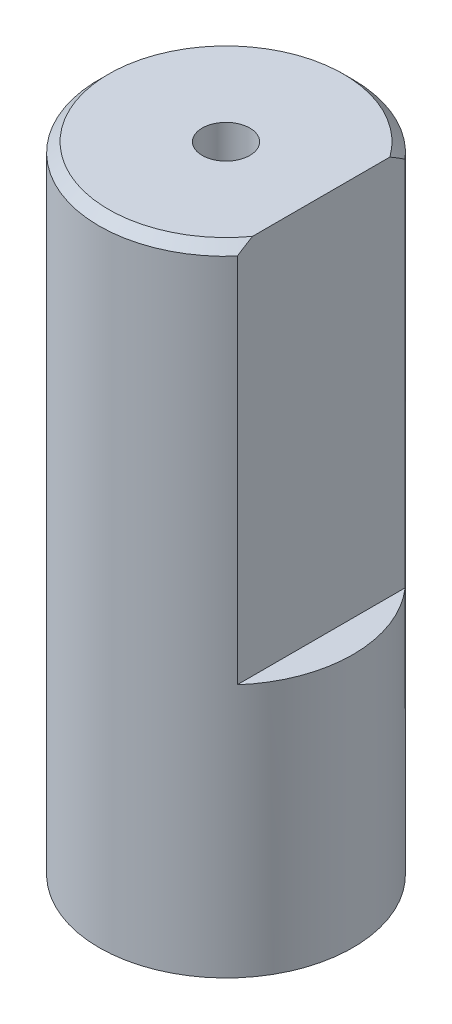
SolidWorks part; units mm, degrees
ref_plane "Front Plane" through (0, 0, 0) normal (0, 0, 1) x (1, 0, 0)
ref_plane "Top Plane" through (0, 0, 0) normal (0, 1, 0) x (1, 0, 0)
ref_plane "Right Plane" through (0, 0, 0) normal (1, 0, 0) x (0, 0, -1)
sketch "Sketch2" plane through (0, 0, 0) normal (0, 1, 0) x (1, 0, 0)
  circle A0 centre (0, 0) radius 4
  dimension "D1" = 8
extrude "Boss-Extrude1" add sketch "Sketch2" along normal blind 20
sketch "Sketch3" plane through (0, 0, 0) normal (0, 0, 1) x (1, 0, 0)
  line L2 (4, 8) -> (-4, 8)
  line L4 (3, 0) -> (3, 20)
  line L5 (3, 0) -> (3, 20) construction
  line L6 (4, 8) -> (-4, 8) construction
  line L7 (4, 8) -> (3, 8)
  line L8 (4, 8) -> (4, 20)
  line L9 (4, 20) -> (3, 20)
  line L10 (3, 8) -> (3, 20)
  dimension "D1" = 1
  dimension "D2" = 12
extrude "Cut-Extrude2" cut sketch "Sketch3" against normal mid plane 20
chamfer "Chamfer1" distance 0.3 angle 45 1 edges at (-4, 20, 0)
sketch "Sketch4" plane through (0, 20, 0) normal (0, 1, 0) x (1, 0, 0)
  circle A0 centre (0, 0) radius 0.75
  dimension "D1" = 1.5
extrude "Cut-Extrude3" cut sketch "Sketch4" against normal blind 20
